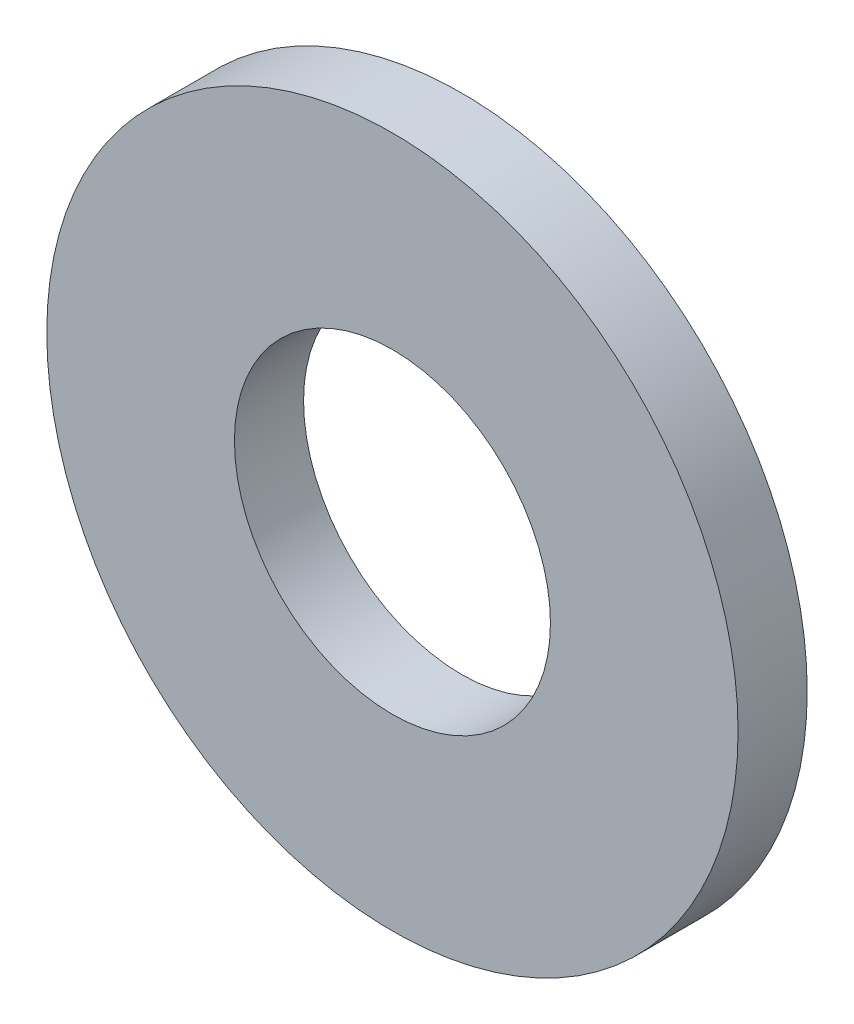
SolidWorks part; units mm, degrees
ref_plane "Спереди" through (0, 0, 0) normal (0, 0, 1) x (1, 0, 0)
ref_plane "Сверху" through (0, 0, 0) normal (0, 1, 0) x (1, 0, 0)
ref_plane "Справа" through (0, 0, 0) normal (1, 0, 0) x (0, 0, -1)
sketch "Эскиз2" plane through (0, 0, 0) normal (0, 0, 1) x (1, 0, 0)
  circle A0 centre (0, 0) radius 3.5
  circle A1 centre (0, 0) radius 1.6
  dimension "D1" = 3.2
  dimension "D2" = 7
extrude "Шайба" add sketch "Эскиз2" along normal blind 0.7
